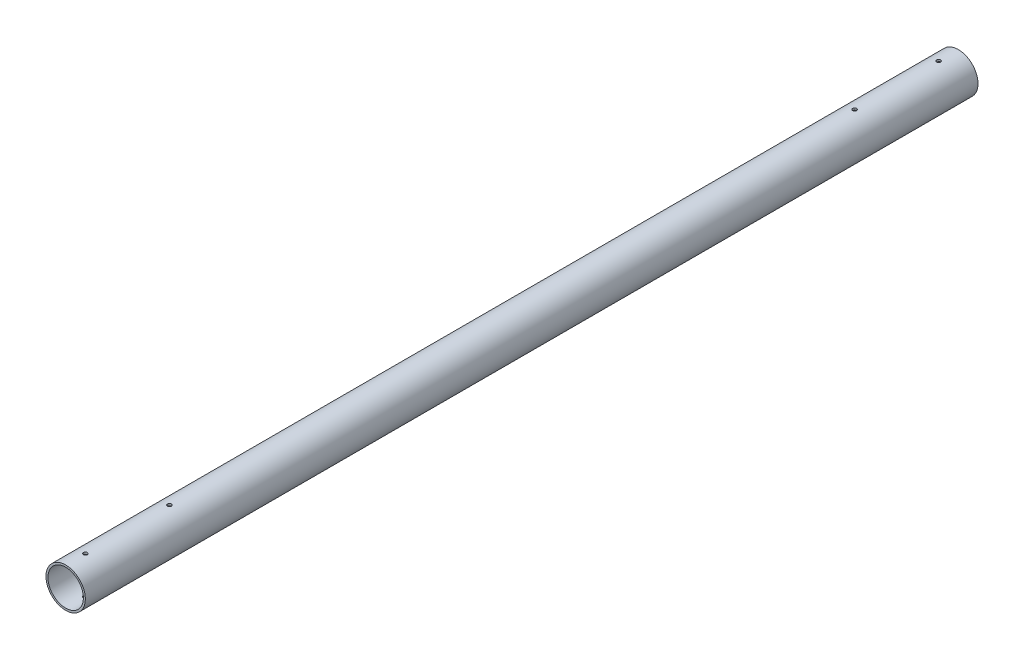
SolidWorks part; units mm, degrees
ref_plane "Front Plane" through (0, 0, 0) normal (0, 0, 1) x (1, 0, 0)
ref_plane "Top Plane" through (0, 0, 0) normal (0, 1, 0) x (1, 0, 0)
ref_plane "Right Plane" through (0, 0, 0) normal (1, 0, 0) x (0, 0, -1)
sketch "Sketch1" plane through (0, 0, 0) normal (0, 0, 1) x (1, 0, 0)
  circle A0 centre (0, 0) radius 15
  dimension "D1" = 30
extrude "Boss-Extrude1" add sketch "Sketch1" along normal blind 680
sketch "Sketch2" plane through (0, 0, 0) normal (0, 0, -1) x (-1, 0, 0)
  circle A0 centre (0, 0) radius 13.5
  dimension "D1" = 27
extrude "Cut-Extrude1" cut sketch "Sketch2" against normal through all
sketch "Sketch3" plane through (0, 0, 0) normal (0, 1, 0) x (1, 0, 0)
  line L0 (-15, -340) -> (25.6457, -340) construction
  line L1 (-15, 0) -> (-15, -680) construction
  line L2 (13.5, 0) -> (-13.5, 0) construction
  line L3 (-15, -680) -> (15, -680) construction
  circle A0 centre (0, -15) radius 1.5
  circle A1 centre (0, -665) radius 1.5
  circle A2 centre (0, -79) radius 1.5
  circle A3 centre (0, -601) radius 1.5
  dimension "D1" = 15
  dimension "D2" = 3
  dimension "D5" = 3
  dimension "D6" = 3
  dimension "D3" = 79
  dimension "D4" = 79
extrude "Cut-Extrude2" cut sketch "Sketch3" against normal through all both and the other way through all
